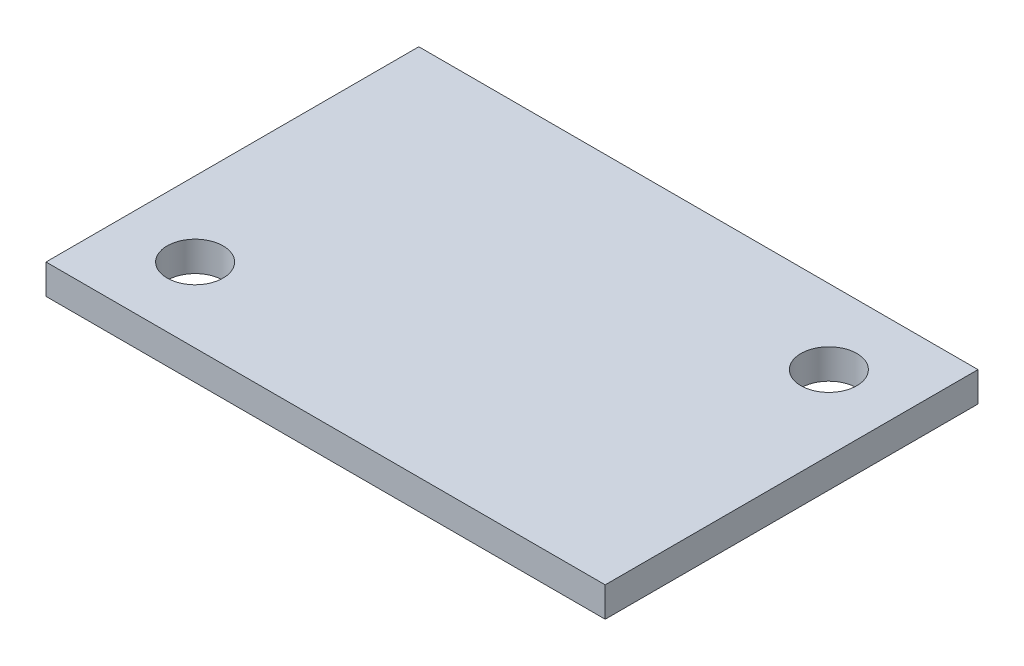
SolidWorks part; units mm, degrees
ref_plane "Front Plane" through (0, 0, 0) normal (0, 0, 1) x (1, 0, 0)
ref_plane "Top Plane" through (0, 0, 0) normal (0, 1, 0) x (1, 0, 0)
ref_plane "Right Plane" through (0, 0, 0) normal (1, 0, 0) x (0, 0, -1)
sketch "Sketch1" plane through (0, 0, 0) normal (0, 1, 0) x (1, 0, 0)
  line L0 (-11, -6) -> (11, 6) construction
  line L1 (15, -10) -> (-15, -10)
  line L2 (15, -10) -> (15, 10)
  line L3 (15, 10) -> (-15, 10)
  line L4 (-15, -10) -> (-15, 10)
  line L5 (15, -10) -> (-15, 10) construction
  line L6 (15, 10) -> (-15, -10) construction
  circle A0 centre (-11, -6) radius 1.5
  circle A1 centre (11, 6) radius 1.5
  point P0 (0, 0)
  point P12 (0, 0)
  dimension "D3" = 3
  dimension "D1" = 30
  dimension "D2" = 20
  dimension "D4" = 4
  dimension "D5" = 4
  dimension "D6" = 2
extrude "Boss-Extrude1" add sketch "Sketch1" along normal blind 1.6
